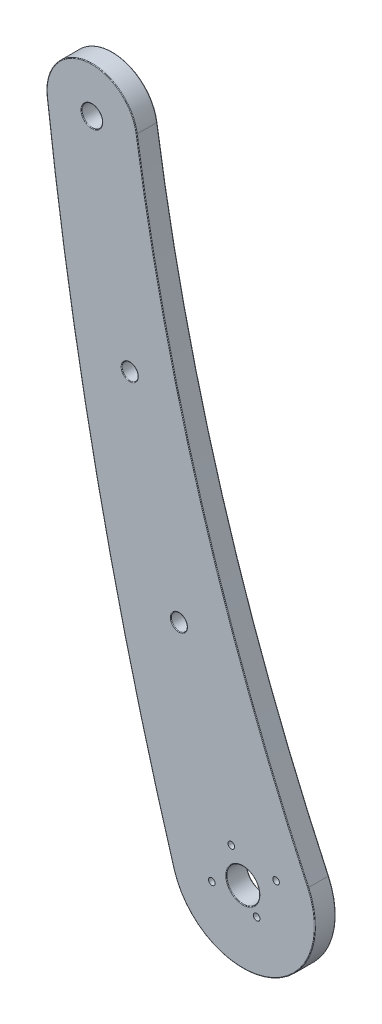
SolidWorks part; units mm, degrees
material "AISI 1020"
ref_plane "Front Plane" through (0, 0, 0) normal (0, 0, 1) x (1, 0, 0)
ref_plane "Top Plane" through (0, 0, 0) normal (0, 1, 0) x (1, 0, 0)
ref_plane "Right Plane" through (0, 0, 0) normal (1, 0, 0) x (0, 0, -1)
sketch "Sketch1" plane through (0, 0, 0) normal (0, 0, 1) x (1, 0, 0)
  line L0 (-20.22, 57.58) -> (-56.8732, 200.9695) construction
  line L1 (-20.22, 57.58) -> (-56.8732, 200.9695) construction
  circle A0 centre (-56.8732, 200.9695) radius 11 construction
  circle A1 centre (-20.22, 57.58) radius 17.5 construction
  circle A2 centre (-56.8732, 200.9695) radius 11 construction
  circle A3 centre (-20.22, 57.58) radius 17.5 construction
  circle A4 centre (-56.8732, 200.9695) radius 2.5
  circle A5 centre (-20.22, 57.58) radius 4
  arc A8 (-45.9959, 202.6076) -> (-4.372, 65.0023) centre (448.4289, 277.0669) ccw
  arc A9 (-67.7968, 199.6753) -> (-36.9637, 52.4908) centre (776.2998, 299.6802) ccw
  arc A10 (-56.8732, 200.9695) -> (-20.22, 57.58) centre (684.5437, 314.111) ccw construction
  arc A11 (-45.9959, 202.6076) -> (-67.7968, 199.6753) centre (-56.8732, 200.9695) ccw
  arc A12 (-36.9637, 52.4908) -> (-4.372, 65.0023) centre (-20.22, 57.58) ccw
  point P17 (-35.7464, 105.1082)
  point P18 (-47.687, 151.8206)
  dimension "D1" = 5
  dimension "D2" = 8
  dimension "D3" = 850
  dimension "D4" = 500
  dimension "D5" = 750
  dimension "D6" = 50
  dimension "D7" = 50
extrude "Boss-Extrude1" add sketch "Sketch1" along normal blind 5
hole_wizard "M3.5 Clearance Hole1" positions "Sketch2" profile "Sketch3" hole size "M3.5" standard "ISO" end condition through all
sketch "Sketch2" plane through (0, 0, 5) normal (0, 0, 1) x (1, 0, 0)
  point P0 (-47.687, 151.8206)
  point P3 (-35.7464, 105.1082)
sketch "Sketch3" plane through (-47.687, 151.8206, 5) normal (1, 0, 0) x (0, -1, 0)
  line L0 (0, 0) -> (0, 5)
  line L1 (0, 5) -> (1.95, 5)
  line L2 (1.95, 5) -> (1.95, 0)
  line L5 (1.95, 0) -> (0, 0)
  line L11 (0, -6.35) -> (0, 107.95) construction
  dimension "Thru Hole Dia." = 3.9
  dimension "Thru Hole Depth" = 5
fillet "Fillet1" radius 0.15 16 edges at (-16.22, 57.58, 0) (-54.3732, 200.9695, 0) (-55.6416, 125.3999, 0) (-13.9483, 41.2425, 0) (-30.1554, 132.3011, 0) (-58.3395, 211.8713, 0) (-33.7964, 105.1082, 0) (-45.737, 151.8206, 0) (-16.22, 57.58, 5) (-30.1554, 132.3011, 5) (-13.9483, 41.2425, 5) (-55.6416, 125.3999, 5) (-58.3395, 211.8713, 5) (-54.3732, 200.9695, 5) (-33.7964, 105.1082, 5) (-45.737, 151.8206, 5)
sketch "Sketch4" plane through (0, 0, 5) normal (0, 0, 1) x (1, 0, 0)
  circle A0 centre (-27.7406, 54.6088) radius 0.8
  circle A1 centre (-16.8774, 52.5801) radius 0.8
  circle A2 centre (-12.1577, 62.5725) radius 0.8
  circle A3 centre (-23.0209, 64.6012) radius 0.8
  dimension "D1" = 1.6
  dimension "D2" = 1.6
  dimension "D3" = 1.6
  dimension "D4" = 1.6
  dimension "D5" = 7.6498
  dimension "D6" = 12.3696
  dimension "D7" = 18.5131
  dimension "D8" = 23.2328
  dimension "D9" = 137.984
  dimension "D10" = 140.0127
  dimension "D11" = 147.9765
  dimension "D12" = 150.0052
extrude "Cut-Extrude1" cut sketch "Sketch4" against normal through all contours A0 | A1 | A3 | A2
